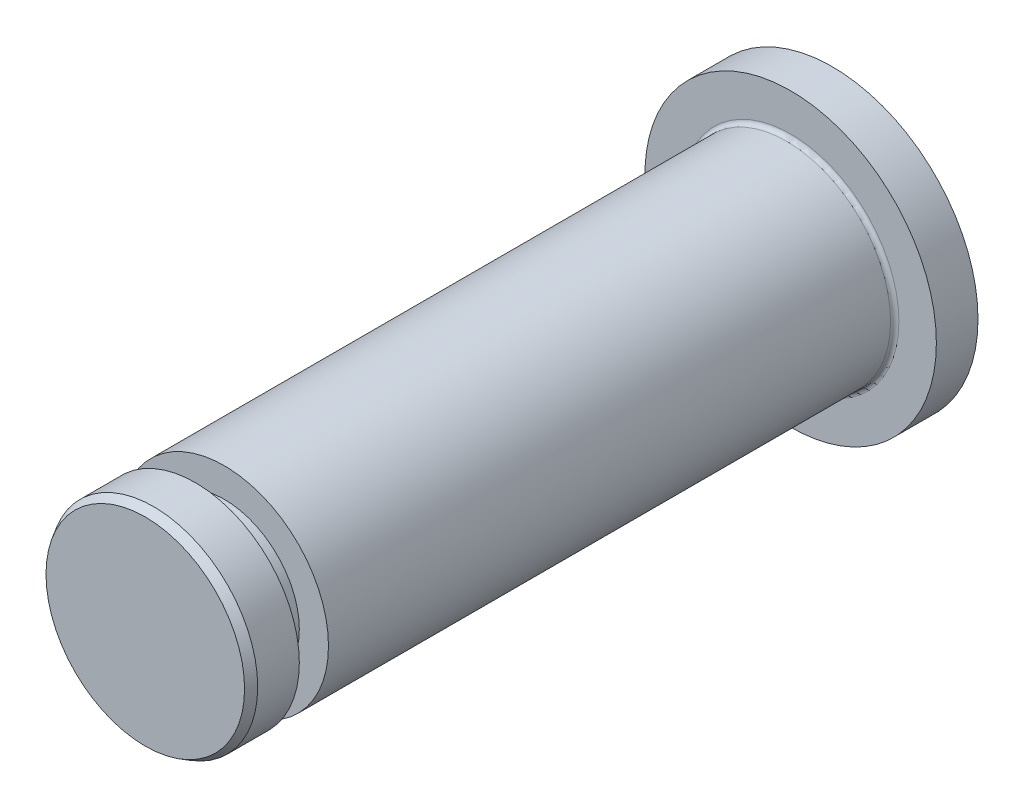
SolidWorks part; units mm, degrees
ref_plane "前视基准面" through (0, 0, 0) normal (0, 0, 1) x (1, 0, 0)
ref_plane "上视基准面" through (0, 0, 0) normal (0, 1, 0) x (1, 0, 0)
ref_plane "右视基准面" through (0, 0, 0) normal (1, 0, 0) x (0, 0, -1)
sketch "草图1" plane through (0, 0, 0) normal (0, 0, 1) x (1, 0, 0)
  circle A0 centre (0, 0) radius 35
  dimension "D1" = 70
extrude "凸台-拉伸1" add sketch "草图1" along normal blind 10
sketch "草图2" plane through (0, 0, 10) normal (0, 0, 1) x (1, 0, 0)
  circle A0 centre (0, 0) radius 25
  dimension "D1" = 50
extrude "凸台-拉伸2" add sketch "草图2" along normal blind 136
sketch "草图3" plane through (0, 0, 146) normal (0, 0, 1) x (1, 0, 0)
  circle A0 centre (0, 0) radius 18
  dimension "D1" = 36
extrude "凸台-拉伸3" add sketch "草图3" along normal blind 7
sketch "草图4" plane through (0, 0, 153) normal (0, 0, 1) x (1, 0, 0)
  circle A0 centre (0, 0) radius 25
  dimension "D1" = 50
extrude "凸台-拉伸4" add sketch "草图4" along normal blind 12
chamfer "倒角1" distance 2 angle 30 1 edges at (25, 0, 165)
fillet "圆角1" radius 1 1 edges at (25, 0, 10)
